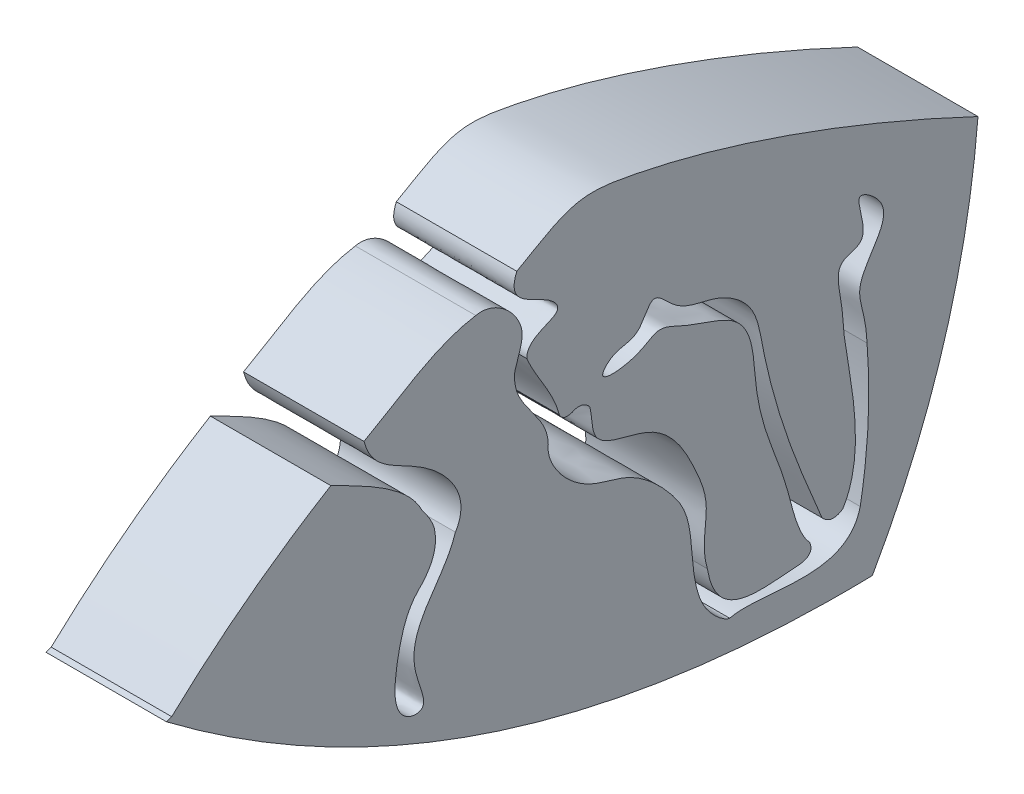
SolidWorks part; units mm, degrees
ref_plane "Front Plane" through (0, 0, 0) normal (0, 0, 1) x (1, 0, 0)
ref_plane "Top Plane" through (0, 0, 0) normal (0, 1, 0) x (1, 0, 0)
ref_plane "Right Plane" through (0, 0, 0) normal (1, 0, 0) x (0, 0, -1)
sketch "Sketch1" plane through (0, 0, 0) normal (1, 0, 0) x (0, 0, -1)
  line L0 (-5.7285, 63.9527) -> (142.5922, 116.011) construction
  spline S0 degree 3 poles (-3.536, 20.2882) (10.0338, 22.9617) (24.4194, 20.401) (34.8511, 11.0027) knots 0.473952 0.473952 0.473952 0.473952 1 1 1 1
  spline S1 degree 2 poles (-32.1844, 0) (-26.2428, 5.5978) (-18.9722, 10.0026) knots 0 0 0 0.556812 0.556812 0.556812
  spline S2 degree 3 poles (34.8511, 9.6274) (28.6552, 12.5696) (18.811, 16.6279) (7.7635, 19.5917) (1.018, 20.6713) (-1.7714, 18.6591) (-3.5358, 17.695) knots 0 0 0 0 0.479063 0.707397 0.794305 0.928423 0.928423 0.928423 0.928423
  spline S3 degree 3 poles (-3.5358, 17.695) (-4.5296, 15.3469) (-1.1459, 15.0998) (0.4832, 12.7185) (-2.7552, 12.3586) (-2.7086, 11.0027) knots 0 0 0 0 0.202924 0.262155 0.36668 0.36668 0.36668 0.36668
  spline S4 degree 3 poles (-11.3955, 4.4253) (-12.6384, 7.0583) (-16.7829, 8.8694) (-18.9722, 10.0026) knots 0.545737 0.545737 0.545737 0.545737 1 1 1 1
  spline S5 degree 3 poles (-16.2184, 11.8062) (-15.5553, 9.2287) (-11.4886, 8.5096) (-7.4954, 4.0296) (-8.456, 1.7557) (-8.6301, 1.4891) knots 0 0 0 0 0.374967 0.716088 0.771729 0.771729 0.771729 0.771729
  spline S6 degree 3 poles (25.5391, -2.0013) (25.5266, -1.5719) (25.3131, 0.4739) (24.5084, 2.0957) (26.1344, 4.674) (27.7424, 7.17) (23.7811, 10.0512) (26.2255, 5.2387) (22.7698, 5.1304) (23.4755, 2.0081) (23.5735, 0.4051) (23.6494, -0.5705) knots 0.103533 0.103533 0.103533 0.103533 0.137225 0.252241 0.335792 0.453099 0.531649 0.649934 0.71225 0.803022 0.912855 0.912855 0.912855 0.912855
  spline S7 degree 2 poles (20.7713, -13.9442) (21.1962, -14.9429) (19.9493, -15.1199) knots 0 0 0 1 1 1
  spline S8 degree 3 poles (12.2827, -11.6021) (11.717, -9.6859) (12.6852, -7.3245) (10.9582, -3.0722) (8.5871, 1.2512) (2.4498, 1.4724) (2.7313, 4.2738) (2.5094, 4.9435) knots 0 0 0 0 0.083394 0.137742 0.243698 0.320986 0.36489 0.36489 0.36489 0.36489
  spline S9 degree 2 poles (-34.739, 1.4891) (-34.9287, -1.085) (-32.1844, 0) knots 0 0 0 1 1 1
  spline S10 degree 2 poles (34.8511, 11.0027) (35.3864, 10.2291) (34.8511, 9.6274) knots 0 0 0 1 1 1
  spline S11 degree 3 poles (25.5391, -2.0013) (25.8519, -5.8607) (25.6632, -9.6834) (24.9731, -13.4694) knots 0.10118 0.10118 0.10118 0.10118 1 1 1 1
  spline S12 degree 3 poles (23.6494, -0.5705) (24.0389, -3.6624) (25.5982, -9.64) (23.5233, -12.9205) knots 0 0 0 0 0.825093 0.825093 0.825093 0.825093
  spline S13 degree 3 poles (-34.739, 1.4891) (-25.3894, 9.098) (-15.8328, 17.8393) (-3.5358, 20.2883) knots 0 0 0 0 1 1 1 1
  spline S14 degree 3 poles (14.1308, -16.0776) (17.0097, -15.407) (23.8631, -17.9738) (24.9731, -13.4694) knots 0 0 0 0 1 1 1 1
  spline S15 degree 3 poles (12.2827, -11.6021) (13.0563, -16.3545) (17.0627, -15.2422) (19.9493, -15.1199) knots 0 0 0 0 0.60965 0.60965 0.60965 0.60965
  spline S16 degree 3 poles (-16.2184, 11.8062) (-12.9776, 13.6069) (-10.3316, 15.6791) (-6.9389, 16.2181) knots 0.635291 0.635291 0.635291 0.635291 1 1 1 1
  spline S17 degree 2 poles (23.5233, -12.9205) (22.5851, -13.5523) (21.8035, -12.7012) knots 0 0 0 1 1 1
  spline S18 degree 3 poles (1.357, 5.3701) (0.5636, 5.0109) (0.218, 5.2096) (0, 5.6071) knots 0.064159 0.064159 0.064159 0.064159 0.436711 0.436711 0.436711 0.436711
  spline S19 degree 3 poles (21.8035, -12.7012) (21.5104, -11.9793) (20.087, -8.61) (18.5489, -4.6366) (16.999, 0.8895) (16.3281, 5.5665) (13.0629, 7.8416) (9.8851, 7.9448) (7.6773, 10.9061) (6.6626, 7.6871) (4.6769, 8.0834) (2.784, 6.0609) (6.5283, 6.4149) (8.2632, 8.0006) (10.5411, 6.5512) (16.1298, 5.2018) (16.0502, -0.0889) (17.0803, -4.373) (19.002, -8.8235) (19.7518, -12.8452) (20.7713, -13.9442) knots 0.043284 0.043284 0.043284 0.043284 0.070188 0.157912 0.259538 0.309962 0.369972 0.421258 0.450241 0.480238 0.514104 0.528943 0.570491 0.596433 0.632482 0.677832 0.763885 0.843045 0.900045 0.955274 0.955274 0.955274 0.955274
  spline S20 degree 3 poles (-0.9223, 3.9434) (-0.997, 6.5501) (-4.0125, 7.7665) (-3.6987, 10.5829) knots 0 0 0 0 1 1 1 1
  spline S21 degree 3 poles (-3.6987, 10.5829) (-3.3887, 11.6778) (-2.2576, 13.6528) (-5.2849, 16.574) (-6.9389, 16.2181) knots 0.684063 0.684063 0.684063 0.684063 0.804598 1 1 1 1
  spline S22 degree 3 poles (-0.9223, 3.9434) (-0.989, 3.466) (-0.4798, 1.5724) (2.2686, -0.9609) (6.1959, -1.4364) (10.151, -5.3975) (11.0185, -7.9389) (11.181, -14.1198) (13.742, -16.0562) (14.1308, -16.0776) knots 0.440867 0.440867 0.440867 0.440867 0.467019 0.535882 0.597258 0.688484 0.789269 0.864222 0.912566 0.912566 0.912566 0.912566
  spline S23 degree 2 poles (2.5094, 4.9435) (2.03, 5.5112) (1.357, 5.3701) knots 0 0 0 1 1 1
  spline S24 degree 3 poles (0, 5.6071) (-0.5105, 7.6047) (-1.9224, 9.1428) (-2.7086, 11.0027) knots 0 0 0 0 1 1 1 1
  spline S25 degree 3 poles (-8.6301, 1.4891) (-9.5705, -1.5271) (-13.6421, -3.9122) (-10.7464, -9.8641) (-12.5589, -10.1167) (-13.8877, -8.678) (-13.4457, -4.7795) (-12.5363, -1.7646) (-11.2394, -0.7356) (-10.9397, -0.247) knots 0 0 0 0 0.334756 0.434438 0.507607 0.625275 0.748217 0.885474 0.947565 0.947565 0.947565 0.947565
  spline S26 degree 2 poles (-10.3977, 2.7203) (-10.6553, 3.5069) (-11.3955, 4.4253) knots 0.955385 0.955385 0.955385 1 1 1
  spline S27 degree 2 poles (-10.3977, 2.7203) (-10.0158, 1.1153) (-10.9397, -0.247) knots 0 0 0 1 1 1
  spline S28 degree 2 poles (34.8511, 11.0027) (33.7518, -5.3013) (25.9817, -18.9405) knots 0 0 0 1 1 1
  spline S29 degree 2 poles (-34.739, 1.4891) (-8.0537, -19.7098) (25.9817, -18.9405) knots 0 0 0 1 1 1
  point P0 (0, 0)
extrude "Boss-Extrude1" add sketch "Sketch1" along normal blind 10 contours S9 S29 S28 S2 S3 S24 S18 S23 S8 S15 S7 S19 S17 S12 S6 S11 S14 S22 S20 S21 S16 S5 S25 S27 S26 S4 S1
